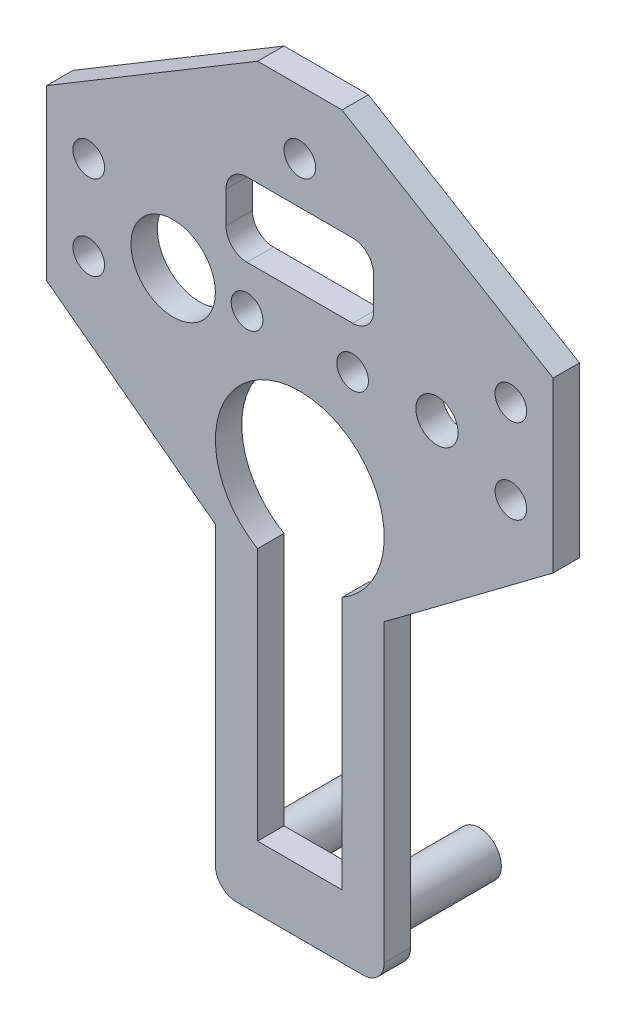
SolidWorks part; units mm, degrees
ref_plane "Front Plane" through (0, 0, 0) normal (0, 0, 1) x (1, 0, 0)
ref_plane "Top Plane" through (0, 0, 0) normal (0, 1, 0) x (1, 0, 0)
ref_plane "Right Plane" through (0, 0, 0) normal (1, 0, 0) x (0, 0, -1)
sketch "Sketch1" plane through (0, 0, 0) normal (0, 0, 1) x (1, 0, 0)
  line L0 (-24, 5.0718) -> (-24, 21.0718)
  line L1 (-24, 21.0718) -> (-4, 33.0718)
  line L2 (-4, 33.0718) -> (4, 33.0718)
  line L3 (4, 33.0718) -> (24, 21.0718)
  line L4 (24, 21.0718) -> (24, 5.0718)
  line L5 (24, 5.0718) -> (8, -6.9282)
  line L6 (8, -6.9282) -> (8, -34.9282)
  line L7 (-6, -36.9282) -> (6, -36.9282)
  line L8 (-8, -34.9282) -> (-8, -6.9282)
  line L9 (-8, -6.9282) -> (-24, 5.0718)
  line L10 (4, -30.9282) -> (-4, -30.9282)
  line L11 (-4, -30.9282) -> (-4, -6.9282)
  line L12 (4, -6.9282) -> (4, -30.9282)
  line L13 (-5, 23.0718) -> (5, 23.0718)
  line L14 (7, 21.0718) -> (7, 18.0718)
  line L15 (-7, 21.0718) -> (-7, 18.0718)
  line L16 (-5, 16.0718) -> (5, 16.0718)
  line L17 (0, 33.0718) -> (0, 8) construction
  arc A0 (-4, -6.9282) -> (4, -6.9282) centre (0, 0) cw
  arc A1 (5, 23.0718) -> (7, 21.0718) centre (5, 21.0718) cw
  arc A2 (-5, 23.0718) -> (-7, 21.0718) centre (-5, 21.0718) ccw
  arc A3 (-7, 18.0718) -> (-5, 16.0718) centre (-5, 18.0718) ccw
  arc A4 (5, 16.0718) -> (7, 18.0718) centre (5, 18.0718) ccw
  circle A5 centre (-12, 12.0718) radius 4
  circle A6 centre (-5, 12.0718) radius 1.5
  circle A7 centre (5, 12.0718) radius 1.5
  circle A8 centre (0, 27.0718) radius 1.5
  circle A9 centre (20, 17.0718) radius 1.5
  circle A10 centre (20, 9.0718) radius 1.5
  circle A11 centre (-20, 17.0718) radius 1.5
  circle A12 centre (-20, 9.0718) radius 1.5
  circle A13 centre (13, 12.0718) radius 2
  arc A14 (-8, -34.9282) -> (-6, -36.9282) centre (-6, -34.9282) ccw
  arc A15 (6, -36.9282) -> (8, -34.9282) centre (6, -34.9282) ccw
  dimension "D1" = 28
  dimension "D4" = 12
  dimension "D7" = 4
  dimension "D8" = 4
  dimension "D9" = 2
  dimension "D10" = 8
  dimension "D19" = 8
  dimension "D20" = 10
  dimension "D22" = 2
  dimension "D18" = 8
  dimension "D24" = 3
  dimension "D25" = 4
  dimension "D31" = 4
  dimension "D3" = 8
  dimension "D5" = 10
  dimension "D6" = 24
  dimension "D11" = 6
  dimension "D12" = 16
  dimension "D13" = 17
  dimension "D14" = 20
  dimension "D15" = 48
  dimension "D16" = 24
  dimension "D17" = 10
  dimension "D21" = 3
  dimension "D23" = 12
  dimension "D26" = 4
  dimension "D27" = 4
  dimension "D28" = 4
  dimension "D29" = 4
  dimension "D30" = 6
  dimension "D32" = 5
  dimension "D33" = 70
  dimension "D34" = 24
  dimension "D35" = 120.964
  dimension "D36" = 11
extrude "Boss-Extrude1" add sketch "Sketch1" along normal blind 2.5
sketch "Sketch2" plane through (0, 0, 0) normal (0, 0, -1) x (-1, 0, 0)
  line L0 (-5, -33.4282) -> (5, -33.4282) construction
  line L1 (6, -36.9282) -> (-6, -36.9282) construction
  circle A0 centre (-5, -33.4282) radius 2.1
  circle A2 centre (5, -33.4282) radius 2.1
  dimension "D1" = 3.5
extrude "Boss-Extrude2" add sketch "Sketch2" along normal blind 9.5
sketch "Sketch4" plane through (0, 0, -9.5) normal (0, 0, -1) x (-1, 0, 0)
  circle A0 centre (-5, -33.4282) radius 1.5
  circle A1 centre (5, -33.4282) radius 1.5
  dimension "D1" = 3
extrude "Cut-Extrude1" cut sketch "Sketch4" against normal blind 5
